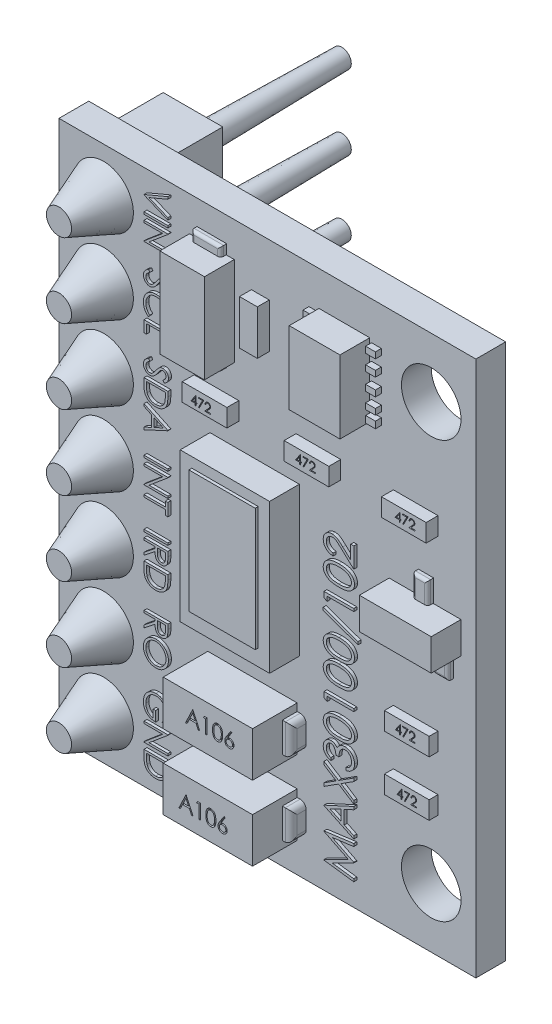
SolidWorks part; units mm, degrees
ref_plane "Ön Düzlem" through (0, 0, 0) normal (0, 0, 1) x (1, 0, 0)
ref_plane "Üst Düzlem" through (0, 0, 0) normal (0, 1, 0) x (1, 0, 0)
ref_plane "Sağ Düzlem" through (0, 0, 0) normal (1, 0, 0) x (0, 0, -1)
sketch "Çizim1" plane through (0, 0, 0) normal (0, 0, 1) x (1, 0, 0)
  line L1 (0, 0) -> (14, 0)
  line L2 (0, 0) -> (0, 18)
  line L3 (0, 18) -> (14, 18)
  line L4 (14, 0) -> (14, 18)
  dimension "D1" = 14
  dimension "D2" = 18
extrude "Yükseklik-Ekstrüzyon1" add sketch "Çizim1" along normal blind 1
sketch "Çizim2" plane through (0, 0, 1) normal (0, 0, 1) x (1, 0, 0)
  line L0 (14, 18) -> (0, 18) construction
  line L1 (14, 0) -> (14, 18) construction
  line L2 (0, 0) -> (14, 0) construction
  circle A0 centre (12.5, 16) radius 1
  circle A1 centre (12.5, 2) radius 1
  dimension "D2" = 2
  dimension "D4" = 2
  dimension "D1" = 2
  dimension "D3" = 1.5
  dimension "D5" = 1.5
  dimension "D6" = 2
extrude "Kes-Ekstrüzyon1" cut sketch "Çizim2" against normal blind 1
sketch "Çizim3" plane through (0, 0, 1) normal (0, 0, 1) x (1, 0, 0)
  line L0 (0, 18) -> (0, 0) construction
  line L1 (14, 18) -> (0, 18) construction
  circle A0 centre (1.5, 16.5) radius 1
  circle A1 centre (1.5, 14) radius 1
  circle A2 centre (1.5, 11.5) radius 1
  circle A3 centre (1.5, 9) radius 1
  circle A4 centre (1.5, 6.5) radius 1
  circle A5 centre (1.5, 4) radius 1
  circle A6 centre (1.5, 1.5) radius 1
  dimension "D1" = 2
  dimension "D2" = 1.5
  dimension "D3" = 1.5
  dimension "D4" = 7
extrude "Kes-Ekstrüzyon2" cut sketch "Çizim3" against normal through all
sketch "Çizim4" plane through (0, 0, 1) normal (0, 0, 1) x (1, 0, 0)
  line L0 (0, 18) -> (0, 0) construction
  line L1 (5, 1) -> (8, 1)
  line L2 (5, 1) -> (5, 2.5)
  line L3 (5, 2.5) -> (8, 2.5)
  line L4 (8, 1) -> (8, 2.5)
  line L5 (14, 0) -> (14, 18) construction
  line L6 (0, 0) -> (14, 0) construction
  dimension "D1" = 3
  dimension "D2" = 5
  dimension "D3" = 6
  dimension "D4" = 1
  dimension "D5" = 1.5
extrude "Yükseklik-Ekstrüzyon2" add sketch "Çizim4" along normal blind 1.5 separate body
pattern_linear "LÇoğaltma1" count 2 spacing 2.5 along (0, 1, 0) of "Yükseklik-Ekstrüzyon2"
sketch "Çizim6" plane through (0, 0, 1) normal (0, 0, 1) x (1, 0, 0)
  line L0 (5, 2.5) -> (5, 1) construction
  line L1 (5, 2.25) -> (4.7, 2.25)
  line L2 (5, 2.25) -> (5, 1.25)
  line L3 (5, 1.25) -> (4.7, 1.25)
  line L4 (4.7, 2.25) -> (4.7, 1.25)
  line L5 (8, 2.5) -> (5, 2.5) construction
  line L6 (5, 1) -> (8, 1) construction
  dimension "D1" = 0.3
  dimension "D2" = 0.25
  dimension "D3" = 0.25
extrude "Yükseklik-Ekstrüzyon3" add sketch "Çizim6" along normal blind 0.5 separate body
fillet "Radyus1" radius 0.2 3 edges at (4.7, 1.25, 1.25) (4.7, 2.25, 1.25) (4.7, 1.75, 1.5)
sketch "Çizim7" plane through (0, 0, 1) normal (0, 0, 1) x (1, 0, 0)
  line L0 (8, 1) -> (8, 2.5) construction
  line L1 (8, 2.25) -> (8.3, 2.25)
  line L2 (8, 2.25) -> (8, 1.25)
  line L3 (8, 1.25) -> (8.3, 1.25)
  line L4 (8.3, 2.25) -> (8.3, 1.25)
  line L5 (8, 3.5) -> (8, 5) construction
  line L6 (8, 4.75) -> (8.3, 4.75)
  line L7 (8, 4.75) -> (8, 3.75)
  line L8 (8, 3.75) -> (8.3, 3.75)
  line L9 (8.3, 4.75) -> (8.3, 3.75)
  line L10 (5, 5) -> (5, 3.5) construction
  line L11 (5, 4.75) -> (4.7, 4.75)
  line L12 (5, 4.75) -> (5, 3.75)
  line L13 (5, 3.75) -> (4.7, 3.75)
  line L14 (4.7, 4.75) -> (4.7, 3.75)
  line L15 (5, 3.5) -> (8, 3.5) construction
  line L16 (8, 5) -> (5, 5) construction
  line L17 (8, 5) -> (5, 5) construction
  line L18 (5, 3.5) -> (8, 3.5) construction
  line L19 (8, 2.5) -> (5, 2.5) construction
  line L20 (5, 1) -> (8, 1) construction
  dimension "D1" = 0.25
  dimension "D2" = 0.25
  dimension "D3" = 0.3
  dimension "D4" = 0.25
  dimension "D5" = 0.25
  dimension "D6" = 0.3
  dimension "D7" = 0.3
  dimension "D8" = 0.25
  dimension "D9" = 0.25
extrude "Yükseklik-Ekstrüzyon4" add sketch "Çizim7" along normal blind 0.5 separate body
fillet "Radyus2" radius 0.2 3 edges at (4.7, 4.75, 1.25) (4.7, 3.75, 1.25) (4.7, 4.25, 1.5)
fillet "Radyus3" radius 0.2 3 edges at (8.3, 4.75, 1.25) (8.3, 3.75, 1.25) (8.3, 4.25, 1.5)
fillet "Radyus4" radius 0.2 3 edges at (8.3, 1.25, 1.25) (8.3, 2.25, 1.25) (8.3, 1.75, 1.5)
sketch "Çizim8" plane through (0, 0, 2.5) normal (0, 0, 1) x (1, 0, 0)
  text T0 "A106" font "Century Gothic" height 0.5
extrude "Kes-Ekstrüzyon3" cut sketch "Çizim8" against normal blind 0.1
sketch "Çizim9" plane through (0, 0, 2.5) normal (0, 0, 1) x (1, 0, 0)
  text T0 "A106" font "Century Gothic" height 0.5
extrude "Kes-Ekstrüzyon4" cut sketch "Çizim9" against normal blind 0.1
sketch "Çizim10" plane through (0, 0, 1) normal (0, 0, 1) x (1, 0, 0)
  line L1 (5.0712, 6.395) -> (8.0712, 6.395)
  line L2 (5.0712, 6.395) -> (5.0712, 11.395)
  line L3 (5.0712, 11.395) -> (8.0712, 11.395)
  line L4 (8.0712, 6.395) -> (8.0712, 11.395)
  dimension "D1" = 5
  dimension "D2" = 3
extrude "Yükseklik-Ekstrüzyon5" add sketch "Çizim10" along normal blind 1 separate body
sketch "Çizim11" plane through (0, 0, 2) normal (0, 0, 1) x (1, 0, 0)
  line L1 (5.462, 6.9429) -> (7.6921, 6.9429)
  line L2 (5.462, 6.9429) -> (5.462, 11.0571)
  line L3 (5.462, 11.0571) -> (7.6921, 11.0571)
  line L4 (7.6921, 6.9429) -> (7.6921, 11.0571)
extrude "Yükseklik-Ekstrüzyon6" add sketch "Çizim11" along normal blind 0.1 separate body
sketch "Çizim12" plane through (0, 0, 1) normal (0, 0, 1) x (1, 0, 0)
  line L1 (4.3864, 16.8375) -> (5.8864, 16.8375)
  line L2 (4.3864, 16.8375) -> (4.3864, 13.8375)
  line L3 (4.3864, 13.8375) -> (5.8864, 13.8375)
  line L4 (5.8864, 16.8375) -> (5.8864, 13.8375)
  line L5 (8.7323, 16.8375) -> (10.4362, 16.8375)
  line L6 (8.7323, 16.8375) -> (8.7323, 14.3917)
  line L7 (8.7323, 14.3917) -> (10.4362, 14.3917)
  line L8 (10.4362, 16.8375) -> (10.4362, 14.3917)
  line L9 (11.0883, 10.1755) -> (13.5, 10.1755)
  line L10 (11.0883, 10.1755) -> (11.0883, 9.1147)
  line L11 (11.0883, 9.1147) -> (13.5, 9.1147)
  line L12 (13.5, 10.1755) -> (13.5, 9.1147)
  dimension "D1" = 1.5
  dimension "D2" = 3
extrude "Yükseklik-Ekstrüzyon7" add sketch "Çizim12" along normal blind 1 separate body
sketch "Çizim13" plane through (0, 0, 1) normal (0, 0, 1) x (1, 0, 0)
  line L0 (4.3864, 13.8375) -> (5.8864, 13.8375) construction
  line L1 (5.6301, 16.852) -> (4.6363, 16.852)
  line L2 (5.6301, 16.852) -> (5.6301, 17.1697)
  line L3 (5.6301, 17.1697) -> (4.6363, 17.1697)
  line L4 (4.6363, 16.852) -> (4.6363, 17.1697)
  line L5 (5.6301, 13.8375) -> (4.6363, 13.8375)
  line L6 (5.6301, 13.8375) -> (5.6301, 13.5667)
  line L7 (5.6301, 13.5667) -> (4.6363, 13.5667)
  line L8 (4.6363, 13.8375) -> (4.6363, 13.5667)
  line L10 (8.7494, 16.7216) -> (8.3931, 16.7216)
  line L11 (8.7494, 16.7216) -> (8.7494, 16.5154)
  line L12 (8.7494, 16.5154) -> (8.3931, 16.5154)
  line L13 (8.3931, 16.7216) -> (8.3931, 16.5154)
  line L14 (8.7494, 16.1823) -> (8.3931, 16.1823)
  line L15 (8.7494, 16.1823) -> (8.7494, 15.9837)
  line L16 (8.7494, 15.9837) -> (8.3931, 15.9837)
  line L17 (8.3931, 16.1823) -> (8.3931, 15.9837)
  line L18 (8.7494, 15.6134) -> (8.3931, 15.6134)
  line L19 (8.7494, 15.6134) -> (8.7494, 15.4089)
  line L20 (8.7494, 15.4089) -> (8.3931, 15.4089)
  line L21 (8.3931, 15.6134) -> (8.3931, 15.4089)
  line L22 (8.7494, 15.0738) -> (8.3931, 15.0738)
  line L23 (8.7494, 15.0738) -> (8.7494, 14.8776)
  line L24 (8.7494, 14.8776) -> (8.3931, 14.8776)
  line L25 (8.3931, 15.0738) -> (8.3931, 14.8776)
  line L26 (8.7494, 14.7073) -> (8.3931, 14.7073)
  line L27 (8.7494, 14.7073) -> (8.7494, 14.4827)
  line L28 (8.7494, 14.4827) -> (8.3931, 14.4827)
  line L29 (8.3931, 14.7073) -> (8.3931, 14.4827)
  line L30 (10.4959, 14.4827) -> (10.8258, 14.4827)
  line L31 (10.4959, 14.4827) -> (10.4959, 14.7073)
  line L32 (10.4959, 14.7073) -> (10.8258, 14.7073)
  line L33 (10.8258, 14.4827) -> (10.8258, 14.7073)
  line L34 (10.4959, 14.8776) -> (10.8258, 14.8776)
  line L35 (10.4959, 14.8776) -> (10.4959, 15.0738)
  line L36 (10.4959, 15.0738) -> (10.8258, 15.0738)
  line L37 (10.8258, 14.8776) -> (10.8258, 15.0738)
  line L38 (10.4959, 15.4089) -> (10.8258, 15.4089)
  line L39 (10.4959, 15.4089) -> (10.4959, 15.6134)
  line L40 (10.4959, 15.6134) -> (10.8258, 15.6134)
  line L41 (10.8258, 15.4089) -> (10.8258, 15.6134)
  line L42 (10.4959, 15.9837) -> (10.8258, 15.9837)
  line L43 (10.4959, 15.9837) -> (10.4959, 16.1823)
  line L44 (10.4959, 16.1823) -> (10.8258, 16.1823)
  line L45 (10.8258, 15.9837) -> (10.8258, 16.1823)
  line L46 (10.4959, 16.5154) -> (10.8258, 16.5154)
  line L47 (10.4959, 16.5154) -> (10.4959, 16.7216)
  line L48 (10.4959, 16.7216) -> (10.8258, 16.7216)
  line L49 (10.8258, 16.5154) -> (10.8258, 16.7216)
  line L50 (11.3192, 9.088) -> (11.9118, 9.088)
  line L51 (11.3192, 9.088) -> (11.3192, 8.3388)
  line L52 (11.3192, 8.3388) -> (11.9118, 8.3388)
  line L53 (11.9118, 9.088) -> (11.9118, 8.3388)
  line L54 (12.7606, 9.088) -> (13.2545, 9.088)
  line L55 (12.7606, 9.088) -> (12.7606, 8.3388)
  line L56 (12.7606, 8.3388) -> (13.2545, 8.3388)
  line L57 (13.2545, 9.088) -> (13.2545, 8.3388)
  line L58 (12.069, 10.1942) -> (12.5821, 10.1942)
  line L59 (12.069, 10.1942) -> (12.069, 10.9251)
  line L60 (12.069, 10.9251) -> (12.5821, 10.9251)
  line L61 (12.5821, 10.1942) -> (12.5821, 10.9251)
extrude "Yükseklik-Ekstrüzyon8" add sketch "Çizim13" along normal blind 0.2 separate body
fillet "Radyus5" radius 0.1 3 edges at (13.2545, 8.7134, 1.2) (12.7606, 8.7134, 1.2) (13.0075, 8.3388, 1.2)
fillet "Radyus6" radius 0.1 3 edges at (11.3192, 8.7134, 1.2) (11.6155, 8.3388, 1.2) (11.9118, 8.7134, 1.2)
fillet "Radyus7" radius 0.1 3 edges at (12.5821, 10.5596, 1.2) (12.3256, 10.9251, 1.2) (12.069, 10.5596, 1.2)
fillet "Radyus8" radius 0.1 3 edges at (4.6363, 17.0108, 1.2) (5.1332, 17.1697, 1.2) (5.6301, 17.0108, 1.2)
sketch "Çizim14" plane through (0, 0, 1) normal (0, 0, 1) x (1, 0, 0)
  line L1 (4.5392, 12.8106) -> (6.0387, 12.8106)
  line L2 (4.5392, 12.8106) -> (4.5392, 12.2106)
  line L3 (4.5392, 12.2106) -> (6.0387, 12.2106)
  line L4 (6.0387, 12.8106) -> (6.0387, 12.2106)
  line L5 (7.9613, 12.8106) -> (9.4613, 12.8106)
  line L6 (7.9613, 12.8106) -> (7.9613, 12.2106)
  line L7 (7.9613, 12.2106) -> (9.4613, 12.2106)
  line L8 (9.4613, 12.8106) -> (9.4613, 12.2106)
  line L9 (11.2296, 12.8106) -> (12.7296, 12.8106)
  line L10 (11.2296, 12.8106) -> (11.2296, 12.2106)
  line L11 (11.2296, 12.2106) -> (12.7296, 12.2106)
  line L12 (12.7296, 12.8106) -> (12.7296, 12.2106)
  line L13 (6.4617, 16.2484) -> (7.0617, 16.2484)
  line L14 (6.4617, 16.2484) -> (6.4617, 14.7484)
  line L15 (6.4617, 14.7484) -> (7.0617, 14.7484)
  line L16 (7.0617, 16.2484) -> (7.0617, 14.7484)
  dimension "D1" = 0.6
  dimension "D2" = 1.4996
  dimension "D3" = 0.6
  dimension "D4" = 1.5
  dimension "D5" = 0.6
  dimension "D6" = 1.5
  dimension "D7" = 0.6
  dimension "D8" = 1.5
extrude "Yükseklik-Ekstrüzyon9" add sketch "Çizim14" along normal blind 0.4 separate body
sketch "Çizim15" plane through (0, 0, 1.4) normal (0, 0, 1) x (1, 0, 0)
  text T0 "472" font "Century Gothic" height 0.3
extrude "Kes-Ekstrüzyon5" cut sketch "Çizim15" against normal blind 0.1
sketch "Çizim16" plane through (0, 0, 1.4) normal (0, 0, 1) x (1, 0, 0)
  text T0 "472                       472" font "Century Gothic" height 0.3
extrude "Kes-Ekstrüzyon6" cut sketch "Çizim16" against normal blind 0.1
sketch "Çizim18" plane through (0, 0, 1) normal (0, 0, 1) x (1, 0, 0)
  line L1 (11.2296, 5.9432) -> (12.7296, 5.9432)
  line L2 (11.2296, 5.9432) -> (11.2296, 6.5432)
  line L3 (11.2296, 6.5432) -> (12.7296, 6.5432)
  line L4 (12.7296, 5.9432) -> (12.7296, 6.5432)
  line L5 (11.2296, 4.6975) -> (12.7296, 4.6975)
  line L6 (11.2296, 4.6975) -> (11.2296, 4.0975)
  line L7 (11.2296, 4.0975) -> (12.7296, 4.0975)
  line L8 (12.7296, 4.6975) -> (12.7296, 4.0975)
  dimension "D1" = 0.6
  dimension "D2" = 0.6
extrude "Yükseklik-Ekstrüzyon10" add sketch "Çizim18" along normal blind 0.3 separate body
sketch "Çizim19" plane through (0, 0, 1.3) normal (0, 0, 1) x (1, 0, 0)
  text T0 "472" font "Century Gothic" height 0.3
extrude "Kes-Ekstrüzyon7" cut sketch "Çizim19" against normal blind 0.1
sketch "Çizim20" plane through (0, 0, 1.3) normal (0, 0, 1) x (1, 0, 0)
  text T0 "472" font "Century Gothic" height 0.3
extrude "Kes-Ekstrüzyon8" cut sketch "Çizim20" against normal blind 0.1
sketch "Çizim21" plane through (0, 0, 1) normal (0, 0, 1) x (1, 0, 0)
  text T0 "  MAX30100/102" font "Century Gothic" height 1
extrude "Yükseklik-Ekstrüzyon11" add sketch "Çizim21" along normal blind 0.1 separate body
sketch "Çizim22" plane through (0, 0, 0) normal (0, 0, -1) x (-1, 0, 0)
  line L0 (-0.5, 13) -> (-2.5, 15) construction
  line L1 (-0.5, 15.5) -> (-2.5, 15.5)
  line L2 (-0.5, 15.5) -> (-0.5, 17.5)
  line L3 (-0.5, 17.5) -> (-2.5, 17.5)
  line L4 (-2.5, 15.5) -> (-2.5, 17.5)
  line L5 (-0.5, 15.5) -> (-2.5, 17.5) construction
  line L6 (-0.5, 17.5) -> (-2.5, 15.5) construction
  line L7 (-0.5, 15) -> (-2.5, 13) construction
  line L8 (-0.5, 13) -> (-0.5, 15)
  line L9 (-0.5, 13) -> (-2.5, 13)
  line L10 (-2.5, 13) -> (-2.5, 15)
  line L11 (-0.5, 15) -> (-2.5, 15)
  line L12 (-0.5, 10.5) -> (-2.5, 12.5) construction
  line L13 (-0.5, 12.5) -> (-2.5, 10.5) construction
  line L14 (-0.5, 10.5) -> (-0.5, 12.5)
  line L15 (-0.5, 10.5) -> (-2.5, 10.5)
  line L16 (-2.5, 10.5) -> (-2.5, 12.5)
  line L17 (-0.5, 12.5) -> (-2.5, 12.5)
  line L18 (-0.5, 8) -> (-2.5, 10) construction
  line L19 (-0.5, 10) -> (-2.5, 8) construction
  line L20 (-0.5, 8) -> (-0.5, 10)
  line L21 (-0.5, 8) -> (-2.5, 8)
  line L22 (-2.5, 8) -> (-2.5, 10)
  line L23 (-0.5, 10) -> (-2.5, 10)
  line L24 (-0.5, 5.5) -> (-2.5, 7.5) construction
  line L25 (-0.5, 7.5) -> (-2.5, 5.5) construction
  line L26 (-0.5, 5.5) -> (-0.5, 7.5)
  line L27 (-0.5, 5.5) -> (-2.5, 5.5)
  line L28 (-2.5, 5.5) -> (-2.5, 7.5)
  line L29 (-0.5, 7.5) -> (-2.5, 7.5)
  line L30 (-0.5, 3) -> (-2.5, 5) construction
  line L31 (-0.5, 5) -> (-2.5, 3) construction
  line L32 (-0.5, 3) -> (-0.5, 5)
  line L33 (-0.5, 3) -> (-2.5, 3)
  line L34 (-2.5, 3) -> (-2.5, 5)
  line L35 (-0.5, 5) -> (-2.5, 5)
  line L36 (-0.5, 0.5) -> (-2.5, 2.5) construction
  line L37 (-0.5, 2.5) -> (-2.5, 0.5) construction
  line L38 (-0.5, 0.5) -> (-0.5, 2.5)
  line L39 (-0.5, 0.5) -> (-2.5, 0.5)
  line L40 (-2.5, 0.5) -> (-2.5, 2.5)
  line L41 (-0.5, 2.5) -> (-2.5, 2.5)
  point P0 (-1.5, 16.5)
  point P8 (-1.5, 14)
  point P13 (-1.5, 11.5)
  point P18 (-1.5, 9)
  point P23 (-1.5, 6.5)
  point P28 (-1.5, 4)
  point P33 (-1.5, 1.5)
  dimension "D1" = 7
extrude "Yükseklik-Ekstrüzyon12" add sketch "Çizim22" along normal blind 2 separate body
sketch "Çizim23" plane through (0, 0, -2) normal (0, 0, -1) x (-1, 0, 0)
  circle A0 centre (-1.5, 16.5) radius 0.4032
  circle A1 centre (-1.5, 14) radius 0.4032
  circle A2 centre (-1.5, 11.5) radius 0.4032
  circle A3 centre (-1.5, 9) radius 0.4032
  circle A4 centre (-1.5, 6.5) radius 0.4032
  circle A5 centre (-1.5, 4) radius 0.4032
  circle A6 centre (-1.5, 1.5) radius 0.4032
  dimension "D1" = 7
extrude "Yükseklik-Ekstrüzyon13" add sketch "Çizim23" along normal blind 5 draft 1 separate body
sketch "Çizim24" plane through (0, 0, 1) normal (0, 0, 1) x (1, 0, 0)
  circle A0 centre (1.5, 16.5) radius 1 construction
  circle A1 centre (1.5, 14) radius 1 construction
  circle A2 centre (1.5, 11.5) radius 1 construction
  circle A3 centre (1.5, 9) radius 1 construction
  circle A4 centre (1.5, 6.5) radius 1 construction
  circle A5 centre (1.5, 4) radius 1 construction
  circle A6 centre (1.5, 1.5) radius 1 construction
  circle A7 centre (1.5, 16.5) radius 1
  circle A8 centre (1.5, 14) radius 1
  circle A9 centre (1.5, 11.5) radius 1
  circle A10 centre (1.5, 9) radius 1
  circle A11 centre (1.5, 6.5) radius 1
  circle A12 centre (1.5, 4) radius 1
  circle A13 centre (1.5, 1.5) radius 1
extrude "Yükseklik-Ekstrüzyon14" add sketch "Çizim24" along normal blind 1.5 draft 21 separate body
sketch "Çizim25" plane through (0, 0, 1) normal (0, 0, 1) x (1, 0, 0)
  text T0 " VIN  SCL  SDA  INT  IRD  RO  GND" font "Century Gothic" height 0.8
extrude "Yükseklik-Ekstrüzyon15" add sketch "Çizim25" along normal blind 0.1 separate body
